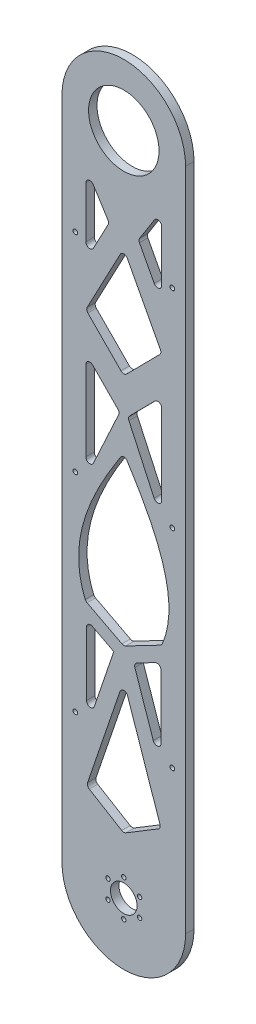
SolidWorks part; units mm, degrees
material "1060 Alloy"
ref_plane "Front Plane" through (0, 0, 0) normal (0, 0, 1) x (1, 0, 0)
ref_plane "Top Plane" through (0, 0, 0) normal (0, 1, 0) x (1, 0, 0)
ref_plane "Right Plane" through (0, 0, 0) normal (1, 0, 0) x (0, 0, -1)
sketch "Sketch2" plane through (0, 0, 0) normal (0, 0, 1) x (1, 0, 0)
  line L0 (0, 0) -> (0, 500) construction
  line L1 (-46.5, 0) -> (-46.5, 500)
  line L2 (46.5, 0) -> (46.5, 500)
  arc A0 (-46.5, 0) -> (46.5, 0) centre (0, 0) ccw
  arc A1 (46.5, 500) -> (-46.5, 500) centre (0, 500) ccw
  circle A2 centre (0, 500) radius 37.25 construction
  circle A3 centre (0, 0) radius 10
  circle A4 centre (0, 13.75) radius 1.65
  circle A5 centre (0, 0) radius 13.75 construction
  circle A6 centre (11.9078, 6.875) radius 1.65
  circle A7 centre (11.9078, -6.875) radius 1.65
  circle A8 centre (0, -13.75) radius 1.65
  circle A9 centre (-11.9078, -6.875) radius 1.65
  circle A10 centre (-11.9078, 6.875) radius 1.65
  point P3 (0, 250)
  point P27 (0, 0)
  dimension "D2" = 74.5
  dimension "D4" = 20
  dimension "D5" = 3.3
  dimension "D6" = 27.5
  dimension "D3" = 46.5
  dimension "D1" = 500
  dimension "D7" = 6
extrude "Boss-Extrude1" add sketch "Sketch2" along normal blind 6.35
sketch "Sketch4" plane through (0, 0, 6.35) normal (0, 0, 1) x (1, 0, 0)
  line L0 (0, 500) -> (0, 999.1647) construction
  line L29 (46.5, 500) -> (-46.5, 500) construction
  line L31 (28.0053, 59.376) -> (0, 42.4117)
  line L32 (0, 141.6934) -> (28.0053, 59.376)
  line L33 (-28.0053, 59.376) -> (0, 141.6934)
  line L34 (0, 42.4117) -> (-28.0053, 59.376)
  line L35 (-7.5, 156.9059) -> (-28.0053, 96.6336)
  line L36 (-28.0053, 167.5829) -> (-7.5, 156.9059)
  line L37 (-28.0053, 96.6336) -> (-28.0053, 167.5829)
  line L38 (28.0053, 167.5829) -> (7.5, 156.9059)
  line L39 (28.0053, 96.6336) -> (28.0053, 167.5829)
  line L40 (7.5, 156.9059) -> (28.0053, 96.6336)
  line L41 (0, 164.2751) -> (28.5505, 179.1412)
  line L42 (0, 164.2751) -> (-28.5505, 179.1412)
  line L43 (28.5505, 259.5868) -> (3, 314.9383)
  line L44 (28.5505, 340.7931) -> (28.5505, 259.5868)
  line L45 (3, 314.9383) -> (28.5505, 340.7931)
  line L46 (-3, 314.9383) -> (-28.5505, 340.7931)
  line L47 (-28.5505, 259.5868) -> (-3, 314.9383)
  line L48 (-28.5505, 340.7931) -> (-28.5505, 259.5868)
  line L49 (0, 423.1428) -> (-28.5505, 369.2462)
  line L50 (-28.5505, 369.2462) -> (0, 340.3557)
  line L51 (0, 340.3557) -> (28.5505, 369.2462)
  line L52 (0, 423.1428) -> (28.5505, 369.2462)
  line L53 (-28.5505, 462.0952) -> (-28.5505, 401.2902)
  line L54 (-11, 434.4215) -> (-28.5505, 462.0952)
  line L55 (-28.5505, 401.2902) -> (-11, 434.4215)
  line L56 (28.5505, 401.2902) -> (11, 434.4215)
  line L57 (28.5505, 462.0952) -> (28.5505, 401.2902)
  line L58 (11, 434.4215) -> (28.5505, 462.0952)
  arc A0 (46.5, 500) -> (-46.5, 500) centre (0, 500) ccw construction
  arc A1 (46.5, 500) -> (-46.5, 500) centre (0, 500) ccw construction
  spline S2 degree 3 poles (28.5505, 179.1412) (45.3203, 216.9857) (19.4301, 259.7903) (0, 290.0258) knots 0 0 0 0 1 1 1 1
  spline S3 degree 3 poles (-28.5505, 179.1412) (-45.3203, 216.9857) (-19.4301, 259.7903) (0, 290.0258) knots 0 0 0 0 1 1 1 1
extrude "Cut-Extrude1" cut sketch "Sketch4" against normal blind 10
fillet "Fillet3" radius 3 29 edges at (-11, 434.4215, 3.175) (-28.5505, 401.2902, 3.175) (28.5505, 401.2902, 3.175) (11, 434.4215, 3.175) (28.5505, 462.0952, 3.175) (-28.5505, 462.0952, 3.175) (0, 423.1428, 3.175) (-28.5505, 369.2462, 3.175) (28.5505, 369.2462, 3.175) (0, 340.3557, 3.175) (28.5505, 340.7931, 3.175) (-28.5505, 340.7931, 3.175) (-3, 314.9383, 3.175) (3, 314.9383, 3.175) (28.5505, 259.5868, 3.175) (-28.5505, 259.5868, 3.175) (28.5505, 179.1412, 3.175) (0, 290.0258, 3.175) (-28.5505, 179.1412, 3.175) (0, 164.2751, 3.175) (-28.0053, 96.6336, 3.175) (28.0053, 96.6336, 3.175) (7.5, 156.9059, 3.175) (-28.0053, 167.5829, 3.175) (28.0053, 167.5829, 3.175) (0, 141.6934, 3.175) (28.0053, 59.376, 3.175) (-28.0053, 59.376, 3.175) (0, 42.4117, 3.175)
sketch "Sketch5" plane through (0, 0, 6.35) normal (0, 0, 1) x (1, 0, 0)
  line L0 (0, -46.5) -> (108.8395, -46.5) construction
  line L1 (46.5, 100) -> (-46.5, 100) construction
  line L2 (46.5, 0) -> (46.5, 500) construction
  line L3 (-46.5, 500) -> (-46.5, 0) construction
  line L4 (-46.5, 106.35) -> (46.5, 106.35) construction
  line L5 (36.5, 106.35) -> (36.5, 100) construction
  line L6 (0, 106.35) -> (0, 100) construction
  line L7 (-46.5, 256.35) -> (46.5, 256.35) construction
  line L8 (-46.5, 181.35) -> (46.5, 181.35) construction
  line L9 (-46.5, 337.7) -> (46.5, 337.7) construction
  arc A1 (-46.5, 0) -> (46.5, 0) centre (0, 0) ccw construction
  circle A2 centre (36.5, 103.175) radius 1.75
  circle A3 centre (-36.5, 103.175) radius 1.75
  circle A4 centre (36.5, 259.525) radius 1.75
  circle A5 centre (-36.5, 259.525) radius 1.75
  circle A6 centre (36.5, 415.875) radius 1.75
  circle A7 centre (-36.5, 415.875) radius 1.75
  point P18 (36.5, 103.175)
  dimension "D2" = 3.5
  dimension "D1" = 146.5
  dimension "D3" = 10
  dimension "D4" = 6.35
  dimension "D5" = 150
  dimension "D6" = 81.35
  dimension "D7" = 81.35
extrude "Cut-Extrude2" cut sketch "Sketch5" against normal through all
sketch "Sketch6" plane through (0, 0, 6.35) normal (0, 0, 1) x (1, 0, 0)
  circle A0 centre (0, 500) radius 26.5
  arc A1 (46.5, 500) -> (-46.5, 500) centre (0, 500) ccw construction
  arc A2 (46.5, 500) -> (-46.5, 500) centre (0, 500) ccw construction
  dimension "D1" = 20
extrude "Cut-Extrude3" cut sketch "Sketch6" against normal blind 10
equation "\"L1L\"=500"
equation "\"L1Thick\"=6.35"
equation "\"D1@Sketch2\"=\"L1L\""
equation "\"Harm-Drive-Outer\"=74.5"
equation "\"D2@Sketch2\"=\"Harm-Drive-Outer\""
equation "\"D1@Boss-Extrude1\"=\"L1Thick\""
